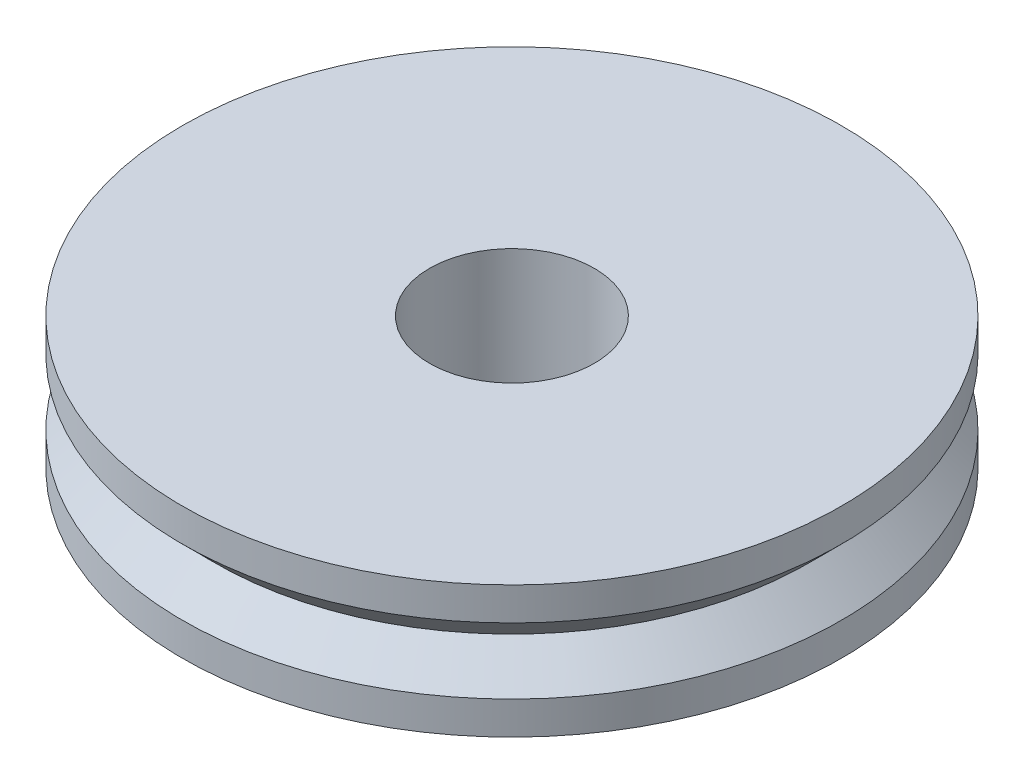
SolidWorks part; units mm, degrees
ref_plane "Plano frontal" through (0, 0, 0) normal (0, 0, 1) x (1, 0, 0)
ref_plane "Plano superior" through (0, 0, 0) normal (0, 1, 0) x (1, 0, 0)
ref_plane "Plano direito" through (0, 0, 0) normal (1, 0, 0) x (0, 0, -1)
sketch "Esboço2" plane through (0, 0, 0) normal (0, 0, 1) x (1, 0, 0)
  line L0 (0, 15.5256) -> (0, -2) construction
  line L1 (10, 0) -> (2.5, 0)
  line L2 (10, 1) -> (10, 0)
  line L3 (10, 1) -> (9, 2)
  line L4 (9, 2) -> (10, 3)
  line L5 (10, 3) -> (10, 4)
  line L6 (10, 4) -> (2.5, 4)
  line L7 (2.5, 4) -> (2.5, 0)
  point P1 (3.6908, 0)
  dimension "D1" = 5
  dimension "D2" = 20
  dimension "D3" = 4
  dimension "D4" = 1
  dimension "D5" = 18
revolve "Revolução1" add sketch "Esboço2" angle 360 about L0
